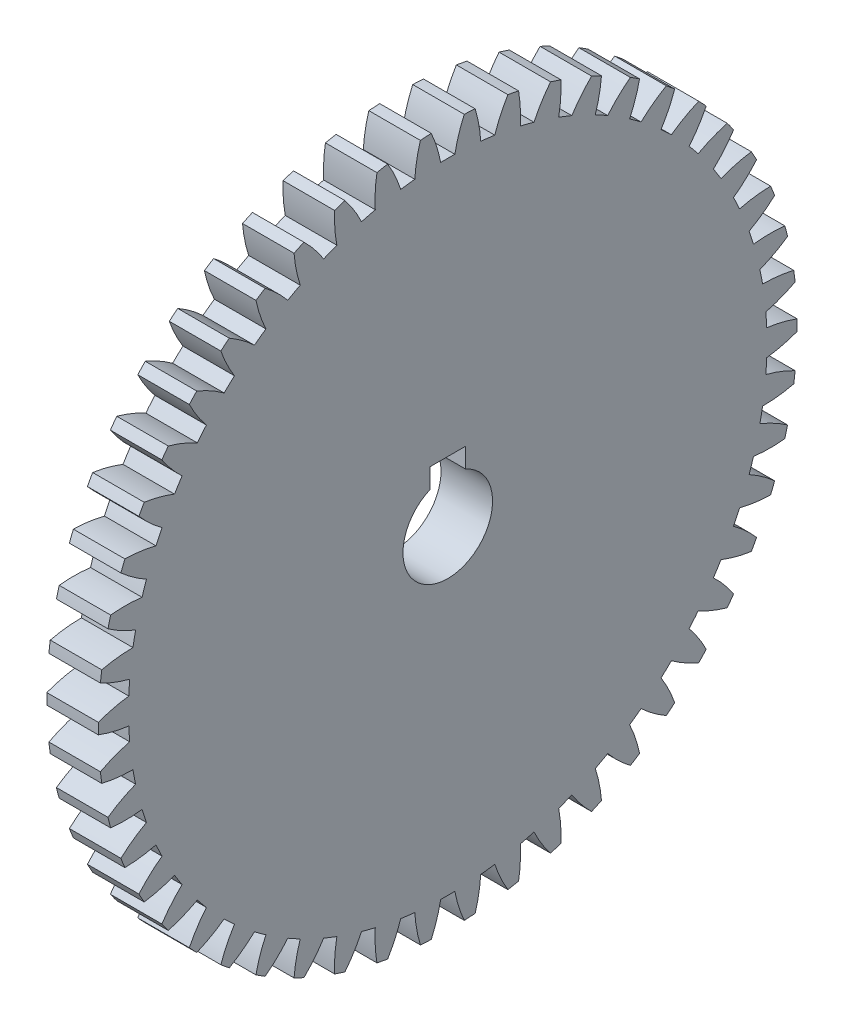
SolidWorks part; units mm, degrees
ref_plane "Plane1" through (0, 0, 0) normal (0, 0, 1) x (1, 0, 0)
ref_plane "Plane2" through (0, 0, 0) normal (0, 1, 0) x (1, 0, 0)
ref_plane "Plane3" through (0, 0, 0) normal (1, 0, 0) x (0, 0, -1)
other "Configuration Table"
sketch "HoldingSke" plane through (0, 0, 0) normal (0, 1, 0) x (1, 0, 0)
  line L0 (0, 0) -> (0.4285, -0.5107)
  line L1 (-15, 0) -> (100, 0) construction
  line L2 (0, 0) -> (-2.1039, 2.3779)
  line L3 (0, 0) -> (-11.863, 4.5341)
  line L4 (0, 0) -> (5.5511, 6.6156)
  line L5 (0, 0) -> (-46.8476, -17.4728)
  line L6 (0, 0) -> (-4.7665, -3.216)
  line L7 (-2.1039, 2.3779) -> (8.6586, 51.2059)
  line L8 (-76.2, 54.61) -> (-74.4, 54.61)
  line L9 (-67.7845, 28.3722) -> (-49.3413, 33.142)
  line L10 (-76.2, 71.12) -> (104.1128, 71.12)
  line L11 (0, 0) -> (-5.75, 0)
  line L12 (-76.2, 101.6) -> (-76.147, 101.6)
  line L13 (24.9733, 27.94) -> (52.9518, 28.4284)
  line L14 (24.9733, 27.94) -> (24.9743, 27.94)
  line L15 (24.9733, 27.94) -> (100.4006, 29.5858)
  line L16 (-63.627, -1.5) -> (-12.827, -1.5)
  circle A0 centre (0, 0) radius 5
  circle A1 centre (0, 0) radius 35.624
  circle A2 centre (0, 0) radius 37.5
  circle A3 centre (0, 0) radius 5
  dimension "Hub_dia" = 75
  dimension "Overall_len" = 50
  dimension "OAL" = 50.0001
  dimension "Ap" = 14.5
  dimension "H" = 19.05
  dimension "Pitch_radius" = 180.3128
  dimension "Addendum_fac" = 1
  dimension "Dedendum_fac" = 1.25
  dimension "Clearance_fac" = 0.25
  dimension "Dedendum_add" = 0.001
sketch "BasProSke" plane through (0, 0, 0) normal (0, 1, 0) x (1, 0, 0)
  line L0 (-10, 0) -> (60, 0) construction
  line L1 (0, 0) -> (0, 39)
  line L2 (0, 0) -> (5.75, 0)
  line L3 (5.75, 0) -> (5.75, 39)
  line L4 (5.75, 39) -> (0, 39)
revolve "Base-Revolve" add sketch "BasProSke" angle 360 about L0
sketch "TooCutSke" plane through (0, 0, 0) normal (1, 0, 0) x (0, 0, -1)
  line L1 (0, 0) -> (0, 107) construction
  line L2 (0, 0) -> (-1.2706, 37.4785) construction
  line L3 (0, 0) -> (-4.7073, 74.8207) construction
  line L4 (-1.2706, 37.4785) -> (-2.3537, 37.4103) construction
  arc A0 (0.7913, 35.6152) -> (-0.7913, 35.6152) centre (0, 0) ccw
  arc A1 (1.8531, 38.9814) -> (-1.8531, 38.9814) centre (0, 0) ccw
  circle A2 centre (0, 0) radius 37.5 construction
  circle A3 centre (0, 0) radius 36.3055 construction
  arc A4 (-0.7913, 35.6152) -> (-1.8531, 38.9814) centre (-15.528, 32.8173) ccw
  arc A5 (1.8531, 38.9814) -> (0.7913, 35.6152) centre (15.528, 32.8173) ccw
extrude "ToothCut" cut sketch "TooCutSke" along normal through all
fillet "Breaks" [suppressed] radius 0.03
fillet "RootFillets" [suppressed] radius 0.376
pattern_circular "TeethCuts" count 50 every 7.2 about axis through (-10, 0, 0) along (1, 0, 0) of "ToothCut", "RootFillets", "Breaks"
sketch "HubNeaOneSke" plane through (0, 0, 0) normal (-1, 0, 0) x (0, 0, 1)
  circle A0 centre (0, 0) radius 35.624
extrude "HubNearOne" [suppressed] add sketch "HubNeaOneSke" along normal blind 44.2501
sketch "HubNeaBotSke" plane through (0, 0, 0) normal (-1, 0, 0) x (0, 0, 1)
  circle A0 centre (0, 0) radius 35.624
extrude "HubNearBoth" [suppressed] add sketch "HubNeaBotSke" along normal blind 22.125
ref_plane "FarPln" through (5.75, 0, 0) normal (1, 0, 0) x (0, 0, -1)
sketch "HubFarSke" plane through (5.75, 0, 0) normal (1, 0, 0) x (0, 0, -1)
  circle A0 centre (0, 0) radius 35.624
extrude "HubFar" [suppressed] add sketch "HubFarSke" along normal blind 22.125
sketch "BorSke" plane through (0, 0, 0) normal (1, 0, 0) x (0, 0, -1)
  circle A0 centre (0, 0) radius 5
extrude "Bore" cut sketch "BorSke" along normal mid plane 100.0001
sketch "KeySke" plane through (0, 0, 0) normal (1, 0, 0) x (0, 0, -1)
  line L0 (-2, 0) -> (-2, 6.8)
  line L1 (-2, 6.8) -> (2, 6.8)
  line L2 (2, 6.8) -> (2, 0)
  line L3 (0, 0) -> (0, 34) construction
  line L4 (-2, 0) -> (2, 0)
extrude "Keyway" cut sketch "KeySke" along normal mid plane 100.0001
pattern_circular "Keyway2" [suppressed] count 2 every 90 about axis through (-10, 0, 0) along (1, 0, 0)
equation "' \"Module@HoldingSke\" = 6.35"
equation "' \"Num_teeth@HoldingSke\" = 12"
equation "' \"Ap@HoldingSke\" =  20"
equation "' \"Ap@HoldingSke\" = 20"
equation "' \"Width@HoldingSke\" = 0.5 * 25.4"
equation "' \"Hub_dia@HoldingSke\"= 1 * 25.4"
equation "' \"Hub_dia@HoldingSke\" = 1 * 25.4"
equation "' \"Overall_len@HoldingSke\" = 1.0 * 25.4"
equation "' \"Bore@HoldingSke\" = 0.75 * 25.4"
equation "' \"T_dim@HoldingSke\" = 0.1 * 25.4"
equation "' \"Width@KeySke\" = 0.25 * 25.4"
equation "' \"Show_teeth@HoldingSke\" = 13"
equation "' \"Backlash@HoldingSke\" = 0.009 * 25.4"
equation "' \"Addendum_fac@HoldingSke\" = 1.0"
equation "' \"Dedendum_fac@HoldingSke\" = 1.25"
equation "' \"Dedendum_add@HoldingSke\" = 0.00005 * 25.4"
equation "' \"Clearance_fac@HoldingSke\" = 0.25"
equation "\"Pitch@HoldingSke\" = 1 / \"Module@HoldingSke\""
equation "\"Overcut_dia@TooCutSke\" = (\"Num_teeth@HoldingSke\" + 2 * \"Addendum_fac@HoldingSke\") / \"Pitch@HoldingSke\" + 0.002 * 25.4"
equation "\"Pitch_dia@TooCutSke\" = \"Num_teeth@HoldingSke\" / \"Pitch@HoldingSke\""
equation "\"Base_dia@TooCutSke\" = \"Num_teeth@HoldingSke\" / \"Pitch@HoldingSke\" * cos((\"Ap@HoldingSke\"  * 3.14159265 / 180))"
equation "\"Root_dia@TooCutSke\" = (\"Num_teeth@HoldingSke\" + 2) / \"Pitch@HoldingSke\" - 2 * (\"Addendum_fac@HoldingSke\" + \"Dedendum_fac@HoldingSke\") / \"Pitch@HoldingSke\" - \"Dedendum_add@HoldingSke\" * 2"
equation "\"Half_ang@TooCutSke\" = 180 / \"Num_teeth@HoldingSke\""
equation "\"Half_CT@TooCutSke\" = \"Num_teeth@HoldingSke\" / \"Pitch@HoldingSke\" * sin((3.14159265 / 2 / \"Num_teeth@HoldingSke\")) / 2 - 7 * \"Backlash@HoldingSke\" / 4"
equation "\"Flank_rad@TooCutSke\" = \"Num_teeth@HoldingSke\" / \"Pitch@HoldingSke\" / 5"
equation "\"Radius@RootFillets\" = \"Clearance_fac@HoldingSke\" / \"Pitch@HoldingSke\" + \"Dedendum_add@HoldingSke\""
equation "\"Break_rad@Breaks\" = 0.02 / \"Pitch@HoldingSke\""
equation "\"Thickness@HoldingSke\" = \"Width@HoldingSke\""
equation "\"OAL@HoldingSke\" = \"Thickness@HoldingSke\""
equation "\"MHD@HoldingSke\" = (\"Num_teeth@HoldingSke\" + 2) / \"Pitch@HoldingSke\" - 2 * (\"Addendum_fac@HoldingSke\" + \"Dedendum_fac@HoldingSke\")  / \"Pitch@HoldingSke\" - \"Dedendum_add@HoldingSke\" * 2"
equation "\"MBD@HoldingSke\" = (\"Num_teeth@HoldingSke\" + 2) / \"Pitch@HoldingSke\" - 2 * (\"Addendum_fac@HoldingSke\" + \"Dedendum_fac@HoldingSke\")  / \"Pitch@HoldingSke\" - \"Dedendum_add@HoldingSke\" * 2 - 0.002 * 25.4"
equation "\"MHD@HoldingSke\" = ((sgn( \"MHD@HoldingSke\" - \"Hub_dia@HoldingSke\" )-1)*( \"MHD@HoldingSke\" - \"Hub_dia@HoldingSke\" ))/-2+ \"Hub_dia@HoldingSke\""
equation "\"MBD@HoldingSke\" = ((sgn( \"MBD@HoldingSke\" - \"Bore@HoldingSke\" )-1)*( \"MBD@HoldingSke\" - \"Bore@HoldingSke\" ))/-2+ \"Bore@HoldingSke\""
equation "\"OAL@HoldingSke\" = ((sgn( \"OAL@HoldingSke\" - \"Overall_len@HoldingSke\" )+1)*( \"OAL@HoldingSke\" - \"Overall_len@HoldingSke\" ))/2 + \"Overall_len@HoldingSke\" + 0.000002 * 25.4"
equation "\"Num_teeth@TeethCuts\" = int( \"Show_teeth@HoldingSke\" ) + 1"
equation "\"Num_teeth@TeethCuts\" = ((sgn( \"Num_teeth@TeethCuts\" - \"Num_teeth@HoldingSke\" )-1)*( \"Num_teeth@TeethCuts\" - \"Num_teeth@HoldingSke\" ))/-2+ \"Num_teeth@HoldingSke\""
equation "\"Num_teeth@TeethCuts\" = ((sgn( \"Num_teeth@TeethCuts\" - 2.0)+1)*( \"Num_teeth@TeethCuts\" - 2.0))/2 +2.0"
equation "\"Angle@TeethCuts\" = 360.0 / \"Num_teeth@HoldingSke\""
equation "\"Diameter@BasProSke\" = (\"Num_teeth@HoldingSke\" + 2 * \"Addendum_fac@HoldingSke\") / \"Pitch@HoldingSke\""
equation "\"Thickness@BasProSke\"  = \"Thickness@HoldingSke\""
equation "' \"Fillet_rad@BasProSke\" =  \"Thickness@HoldingSke\" * 0.05"
equation "' \"Fillet_rad@BasProSke\" = \"Thickness@HoldingSke\" * 0.05"
equation "\"MHD@HoldingSke\" = ((sgn( \"MHD@HoldingSke\" - \"Root_dia@TooCutSke\" )-1)*( \"MHD@HoldingSke\" - \"Root_dia@TooCutSke\" ))/-2+ \"Root_dia@TooCutSke\""
equation "\"Diameter@HubNeaOneSke\" = \"MHD@HoldingSke\""
equation "\"Length@HubNearOne\" = \"OAL@HoldingSke\" - \"Thickness@BasProSke\""
equation "\"Diameter@HubNeaBotSke\" = \"MHD@HoldingSke\""
equation "\"Length@HubNearBoth\" = ( \"OAL@HoldingSke\" - \"Thickness@BasProSke\" ) / 2.0"
equation "\"Thickness@FarPln\" = \"Thickness@BasProSke\""
equation "\"Diameter@HubFarSke\" = \"MHD@HoldingSke\""
equation "\"Length@HubFar\" = ( \"OAL@HoldingSke\" - \"Thickness@BasProSke\" ) / 2.0"
equation "\"Diameter@BorSke\" = \"MBD@HoldingSke\""
equation "\"D1@Bore\" = \"OAL@HoldingSke\" * 2.0"
equation "\"D1@Keyway\" = \"OAL@HoldingSke\" * 2.0"
equation "\"Offset@KeySke\" = \"T_dim@HoldingSke\" + \"MBD@HoldingSke\" / 2.0"
